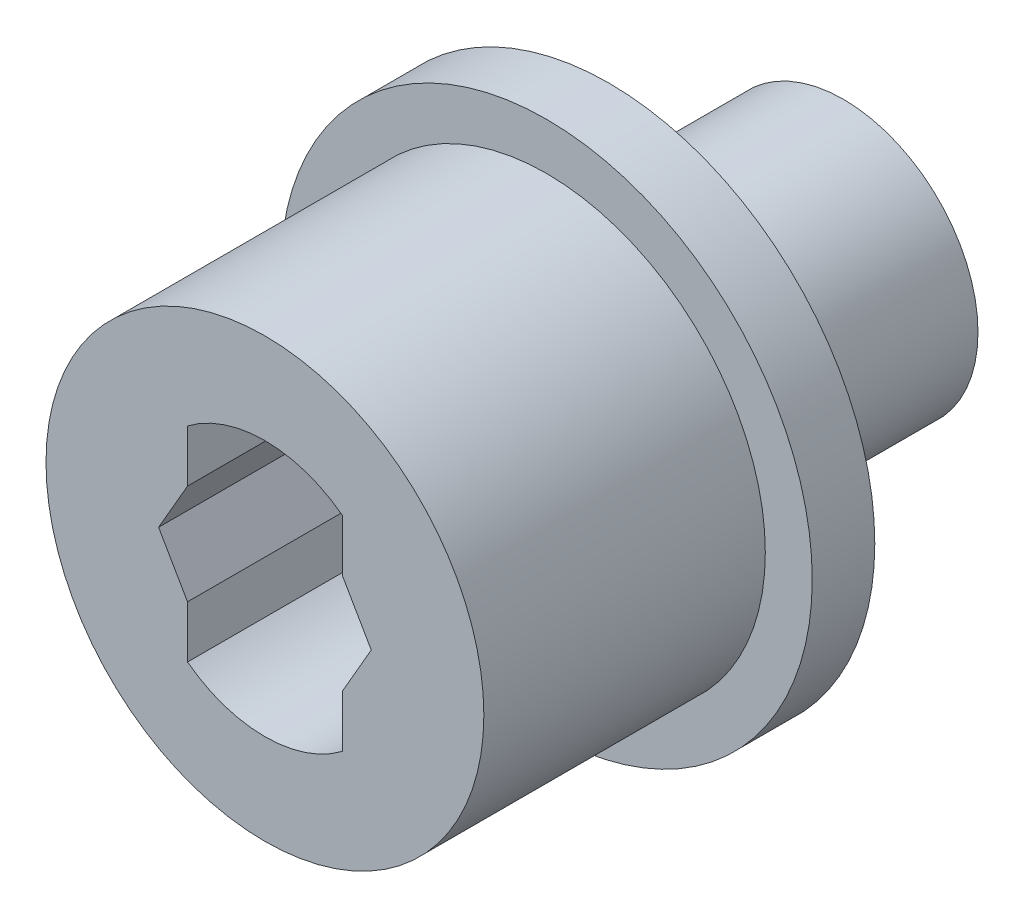
SolidWorks part; units mm, degrees
ref_plane "Front Plane" through (0, 0, 0) normal (0, 0, 1) x (1, 0, 0)
ref_plane "Top Plane" through (0, 0, 0) normal (0, 1, 0) x (1, 0, 0)
ref_plane "Right Plane" through (0, 0, 0) normal (1, 0, 0) x (0, 0, -1)
sketch "Sketch1" plane through (0, 0, 0) normal (0, 0, 1) x (1, 0, 0)
  line L0 (-2.475, 3.2687) -> (-2.475, -3.2687)
  line L1 (2.475, 3.2687) -> (2.475, -3.2687)
  circle A0 centre (0, 0) radius 7
  circle A1 centre (0, 0) radius 4.1
  dimension "D1" = 8.2
  dimension "D2" = 14
  dimension "D3" = 4.95
extrude "Boss-Extrude1" add sketch "Sketch1" along normal blind 9 contours A0 A1 | L0 A1 | L1 A1
sketch "Sketch5" plane through (0, 0, 0) normal (0, 0, -1) x (-1, 0, 0)
  circle A0 centre (0, 0) radius 8.5
  dimension "D1" = 17
extrude "Boss-Extrude3" add sketch "Sketch5" along normal blind 2
sketch "Sketch6" plane through (0, 0, -2) normal (0, 0, -1) x (-1, 0, 0)
  circle A0 centre (0, 0) radius 3.45
sketch "Sketch9" plane through (0, 0, 0) normal (0, 0, 1) x (1, 0, 0)
  line L1 (-3.4, 0) -> (-1.7, -2.9445)
  line L2 (-1.7, -2.9445) -> (1.7, -2.9445)
  line L3 (1.7, -2.9445) -> (3.4, 0)
  line L4 (3.4, 0) -> (1.7, 2.9445)
  line L5 (1.7, 2.9445) -> (-1.7, 2.9445)
  line L6 (-1.7, 2.9445) -> (-3.4, 0)
  circle A0 centre (0, 0) radius 3.4 construction
extrude "Cut-Extrude4" cut sketch "Sketch9" along normal through all
sketch "Sketch10" plane through (0, 0, -2) normal (0, 0, -1) x (-1, 0, 0)
  circle A0 centre (0, 0) radius 4.3
extrude "Boss-Extrude4" add sketch "Sketch10" along normal blind 7.5
extrude "Cut-Extrude8" cut sketch "Sketch6" against normal blind 1 and the other way through all
